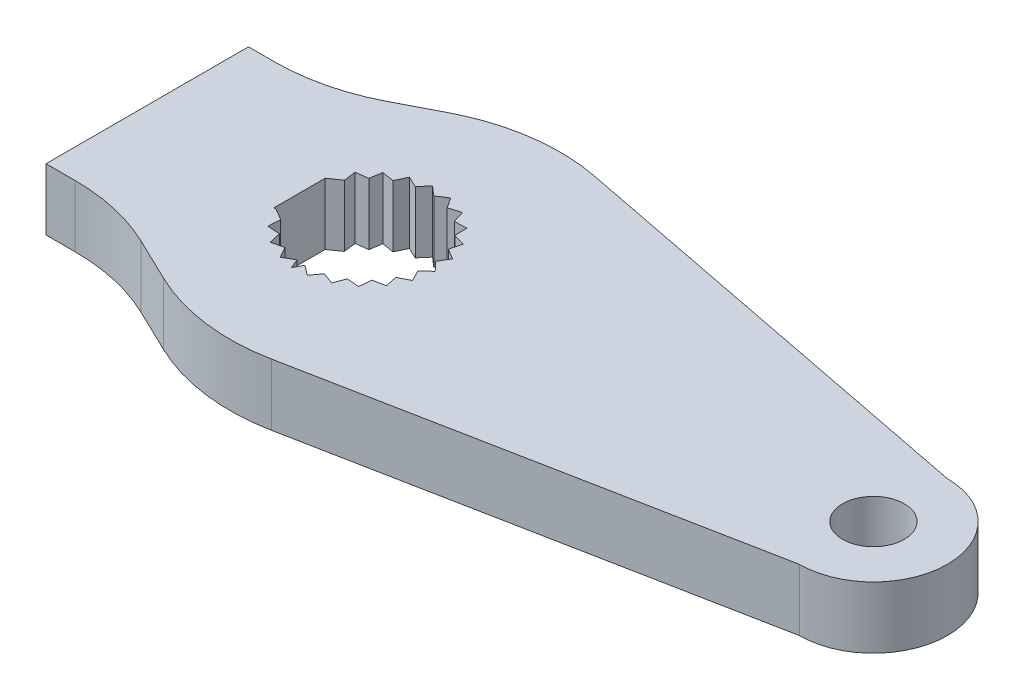
SolidWorks part; units mm, degrees
ref_plane "Front Plane" through (0, 0, 0) normal (0, 0, 1) x (1, 0, 0)
ref_plane "Top Plane" through (0, 0, 0) normal (0, 1, 0) x (1, 0, 0)
ref_plane "Right Plane" through (0, 0, 0) normal (1, 0, 0) x (0, 0, -1)
sketch "Sketch1" plane through (0, 0, 0) normal (0, 1, 0) x (1, 0, 0)
  line L0 (-25.1728, -2.8548) -> (-23.9794, -3.5543)
  line L1 (-24.0454, -4.8148) -> (-22.785, -4.8808)
  line L2 (-23.9794, -3.5543) -> (-24.0454, -4.8148)
  line L3 (-24.3704, 4.4907) -> (-24.2166, 3.2379)
  line L4 (-24.2166, 3.2379) -> (-25.3784, 2.4127)
  line L5 (-23.1176, 4.6445) -> (-24.3704, 4.4907)
  line L6 (-21.1402, 6.8376) -> (-21.6736, 5.6937)
  line L7 (-22.9202, 5.8911) -> (-23.1176, 4.6445)
  line L8 (-21.6736, 5.6937) -> (-22.9202, 5.8911)
  line L9 (-19.9963, 6.3042) -> (-21.1402, 6.8376)
  line L10 (-17.1572, 7.1161) -> (-18.2157, 6.4287)
  line L11 (-19.1682, 7.2567) -> (-19.9963, 6.3042)
  line L12 (-18.2157, 6.4287) -> (-19.1682, 7.2567)
  line L13 (-16.4697, 6.0576) -> (-17.1572, 7.1161)
  line L14 (-13.6318, 5.2416) -> (-14.8937, 5.2196)
  line L15 (-15.2627, 6.4266) -> (-16.4697, 6.0576)
  line L16 (-14.8937, 5.2196) -> (-15.2627, 6.4266)
  line L17 (-11.6354, 1.7838) -> (-12.7173, 2.4338)
  line L18 (-12.3906, 3.653) -> (-13.6097, 3.9796)
  line L19 (-12.7173, 2.4338) -> (-12.3906, 3.653)
  line L20 (-13.6097, 3.9796) -> (-13.6318, 5.2416)
  line L21 (-11.7747, -2.2065) -> (-12.3477, -1.082)
  line L22 (-11.4247, -0.2212) -> (-12.2854, 0.7019)
  line L23 (-12.3477, -1.082) -> (-11.4247, -0.2212)
  line L24 (-12.2854, 0.7019) -> (-11.6354, 1.7838)
  line L25 (-14.0075, -5.5167) -> (-13.8974, -4.2593)
  line L26 (-12.6585, -4.0185) -> (-12.8993, -2.7795)
  line L27 (-13.8974, -4.2593) -> (-12.6585, -4.0185)
  line L28 (-12.8993, -2.7795) -> (-11.7747, -2.2065)
  line L29 (-17.655, -7.1407) -> (-16.8954, -6.1327)
  line L30 (-15.7171, -6.585) -> (-15.2648, -5.4067)
  line L31 (-16.8954, -6.1327) -> (-15.7171, -6.585)
  line L32 (-15.2648, -5.4067) -> (-14.0075, -5.5167)
  line L33 (-18.663, -6.3811) -> (-17.655, -7.1407)
  line L34 (-19.5555, -6.3187) -> (-19.1458, -7.2846)
  line L35 (-18.663, -6.3811) -> (-19.1458, -7.2846)
  line L36 (-22.5011, -6.1106) -> (-21.2713, -5.8267)
  line L37 (-20.6594, -6.9306) -> (-19.5555, -6.3187)
  line L38 (-21.2713, -5.8267) -> (-20.6594, -6.9306)
  line L39 (-22.785, -4.8808) -> (-22.5011, -6.1106)
  line L40 (-41.027, 2.5576) -> (-25.3784, 2.4127)
  line L41 (-41.027, -3.0304) -> (-25.1728, -2.8548)
  line L42 (-41.027, -10.6504) -> (-41.027, -3.0304)
  line L43 (-41.027, 2.5576) -> (-41.027, 10.1776)
  line L44 (-41.027, 10.1776) -> (-38.3556, 10.1776)
  line L45 (-41.027, -10.6504) -> (-38.0435, -10.6504)
  line L46 (-29.2294, -12.6616) -> (-24.7442, -14.8208)
  line L47 (-12.0387, -16.4559) -> (33.407, -7.5885)
  line L48 (33.407, 7.6515) -> (-11.7149, 16.4559)
  line L49 (-24.9495, 14.5567) -> (-29.0126, 12.4529)
  arc A0 (33.407, -7.5885) -> (33.407, 7.6515) centre (33.407, 0.0315) ccw
  arc A1 (-24.7442, -14.8208) -> (-12.0387, -16.4559) centre (-15.9301, 3.488) ccw
  arc A2 (-11.7149, 16.4559) -> (-24.9495, 14.5567) centre (-15.6064, -3.488) ccw
  arc A3 (-38.3556, 10.1776) -> (-29.0126, 12.4529) centre (-38.3556, 30.4976) ccw
  arc A4 (-29.2294, -12.6616) -> (-38.0435, -10.6504) centre (-38.0435, -30.9704) ccw
  point P21 (-18.663, 0.0316)
  point P45 (33.407, 0.0315)
extrude "Boss-Extrude1" add sketch "Sketch1" along normal blind 6.35
sketch "Sketch2" plane through (0, 6.35, 0) normal (0, 1, 0) x (1, 0, 0)
  circle A0 centre (33.407, 0.0315) radius 3.175
  point P2 (0, 0)
  dimension "D1" = 6.35
extrude "Cut-Extrude1" cut sketch "Sketch2" against normal up to next
sketch "Sketch3" plane through (0, 0, 0) normal (0, 0, 1) x (1, 0, 0)
  line L6 (-41.027, 0) -> (-25.3784, 0)
  line L7 (-25.3784, 0) -> (-25.3784, 6.35)
  line L8 (-25.3784, 6.35) -> (-41.027, 6.35)
  line L9 (-41.027, 6.35) -> (-41.027, 0)
  line L10 (-41.027, 0) -> (-25.3784, 0)
  line L11 (-25.3784, 0) -> (-25.3784, 6.35)
  line L12 (-25.3784, 6.35) -> (-41.027, 6.35)
  line L13 (-41.027, 6.35) -> (-41.027, 0)
  point P2 (-37.852, 3.175)
  dimension "D1" = 0
extrude "Boss-Extrude2" add sketch "Sketch3" along normal up to next and the other way up to next
